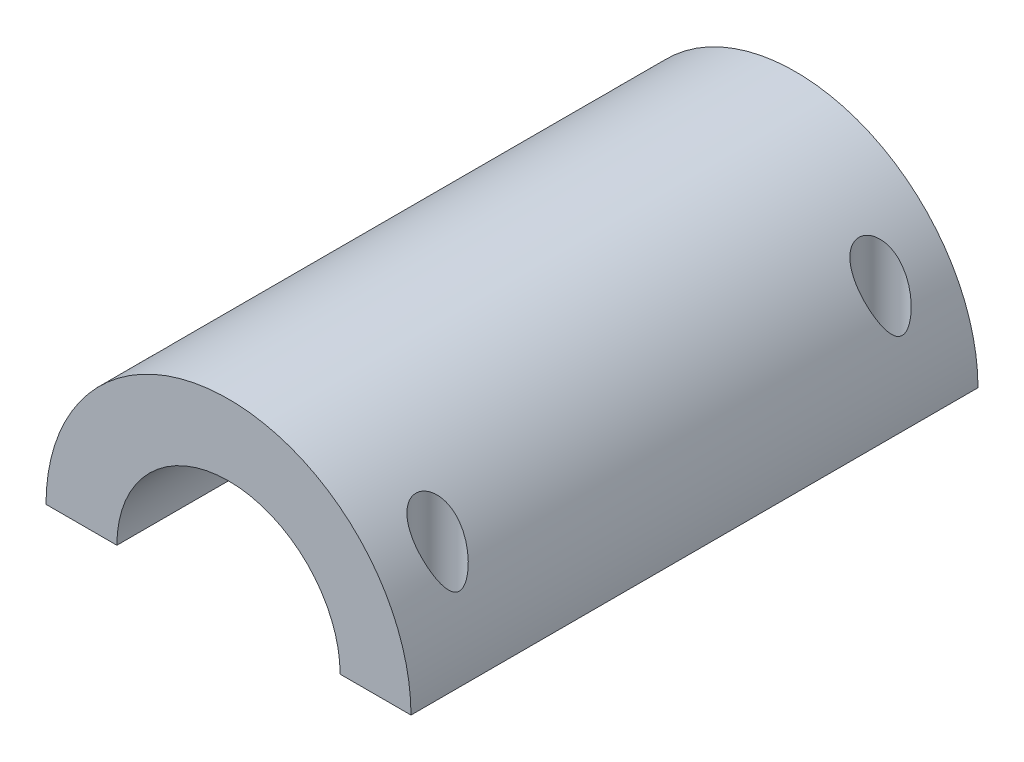
SolidWorks part; units mm, degrees
material "ABS"
ref_plane "Front Plane" through (0, 0, 0) normal (0, 0, 1) x (1, 0, 0)
ref_plane "Top Plane" through (0, 0, 0) normal (0, 1, 0) x (1, 0, 0)
ref_plane "Right Plane" through (0, 0, 0) normal (1, 0, 0) x (0, 0, -1)
sketch "Sketch1" plane through (0, 0, 0) normal (0, 0, 1) x (1, 0, 0)
  line L0 (-20.6, 0) -> (-12.6, 0)
  line L1 (12.6, 0) -> (20.6, 0)
  line L2 (-16.6, 0) -> (-16.6, -50000) construction
  line L3 (16.6, 0) -> (16.6, -50000) construction
  arc A0 (12.6, 0) -> (-12.6, 0) centre (0, 0) ccw
  arc A1 (20.6, 0) -> (-20.6, 0) centre (0, 0) ccw
  point P8 (-16.6, 0)
  point P11 (16.6, 0)
  dimension "D1" = 25.2
  dimension "D2" = 4
extrude "Boss-Extrude1" add sketch "Sketch1" along normal mid plane 64
sketch "Sketch2" plane through (0, 0, 0) normal (0, -1, 0) x (1, 0, 0)
  line L1 (-16.6, -25) -> (16.6, -25)
  line L2 (-16.6, -25) -> (-16.6, 25)
  line L3 (-16.6, 25) -> (16.6, 25)
  line L4 (16.6, -25) -> (16.6, 25)
  line L5 (-16.6, -25) -> (16.6, 25) construction
  line L6 (-16.6, 25) -> (16.6, -25) construction
  point P0 (0, 0)
  point P6 (16.6, 0)
  point P9 (16.6, 25)
  point P10 (-16.6, 25)
  point P11 (16.6, -25)
  point P12 (-16.6, -25)
  dimension "D1" = 50
hole_wizard "CBORE for M3 SHCS1" positions "Sketch2" profile "Sketch3" counterbore size "M3" standard "ANSI Metric"
sketch "Sketch3" plane through (-16.6, 0, -25) normal (1, 0, 0) x (0, 0, -1)
  line L0 (0, 0) -> (0, 20.6)
  line L1 (0, 20.6) -> (2.45, 20.6)
  line L3 (2.45, 20.6) -> (2.45, 0.5)
  line L4 (2.45, 0.5) -> (2.75, 0.5)
  line L5 (2.75, 0.5) -> (2.75, 0)
  line L7 (2.75, 0) -> (0, 0)
  line L11 (0, -6.35) -> (0, 107.95) construction
  dimension "Thru Hole Dia." = 4.9
  dimension "Thru Hole Depth" = 20.6
  dimension "C'Bore Dia." = 5.5
  dimension "C'Bore Depth" = 0.5
